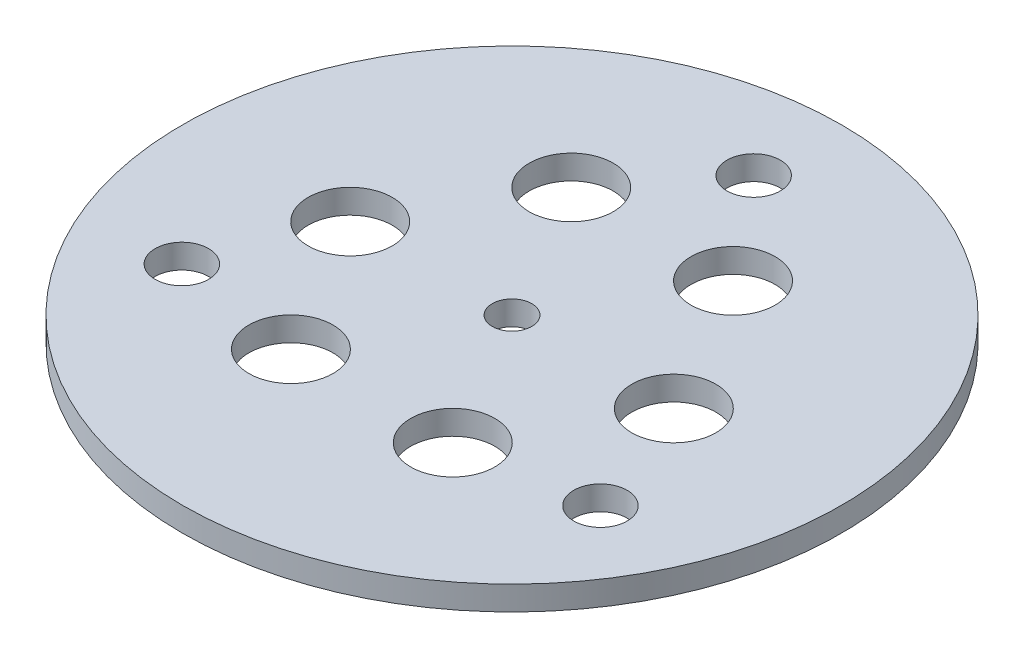
SolidWorks part; units mm, degrees
ref_plane "Front Plane" through (0, 0, 0) normal (0, 0, 1) x (1, 0, 0)
ref_plane "Top Plane" through (0, 0, 0) normal (0, 1, 0) x (1, 0, 0)
ref_plane "Right Plane" through (0, 0, 0) normal (1, 0, 0) x (0, 0, -1)
sketch "Sketch4" plane through (0, 0, 0) normal (0, 1, 0) x (1, 0, 0)
  line L0 (0, 55) -> (0, 0) construction
  line L1 (18.4137, -31.8935) -> (36.8274, 0) construction
  line L2 (36.8274, 0) -> (18.4137, 31.8935) construction
  line L3 (18.4137, 31.8935) -> (-18.4137, 31.8935) construction
  line L4 (-18.4137, 31.8935) -> (-36.8274, 0) construction
  line L5 (-36.8274, 0) -> (-18.4137, -31.8935) construction
  line L6 (-18.4137, -31.8935) -> (18.4137, -31.8935) construction
  line L7 (0, 0) -> (-47.6314, -27.5) construction
  line L8 (0, 0) -> (47.6314, -27.5) construction
  line L20 (5.75, 9.9593) -> (-5.75, 9.9593) construction
  line L21 (-5.75, 9.9593) -> (-11.5, 0) construction
  line L22 (-11.5, 0) -> (-5.75, -9.9593) construction
  line L23 (-5.75, -9.9593) -> (5.75, -9.9593) construction
  line L24 (5.75, -9.9593) -> (11.5, 0) construction
  line L25 (11.5, 0) -> (5.75, 9.9593) construction
  circle A0 centre (0, 0) radius 31.8935 construction
  circle A1 centre (-36.8274, 0) radius 9.575
  circle A2 centre (-18.4137, 31.8935) radius 9.575
  circle A3 centre (18.4137, 31.8935) radius 9.575
  circle A4 centre (36.8274, 0) radius 9.575
  circle A5 centre (18.4137, -31.8935) radius 9.575
  circle A6 centre (-18.4137, -31.8935) radius 9.575
  circle A7 centre (0, 0) radius 75
  circle A11 centre (0, 0) radius 4.5
  circle A18 centre (0, 0) radius 9.9593 construction
  circle A19 centre (0, 55) radius 6.075
  circle A20 centre (47.6314, -27.5) radius 6.075
  circle A21 centre (-47.6314, -27.5) radius 6.075
  point P22 (0, 0)
  point P47 (0, 0)
  point P50 (0, 0)
  point P51 (0, 0)
  point P63 (47.6314, -27.5)
  point P80 (0, 0)
  dimension "D1" = 19.15
  dimension "D3" = 150
  dimension "D6" = 55
  dimension "D11" = 12.15
  dimension "D7" = 9
  dimension "D4" = 120
  dimension "D5" = 120
  dimension "D2" = 6
  dimension "D12" = 3
extrude "Boss-Extrude1" add sketch "Sketch4" along normal blind 5.5
